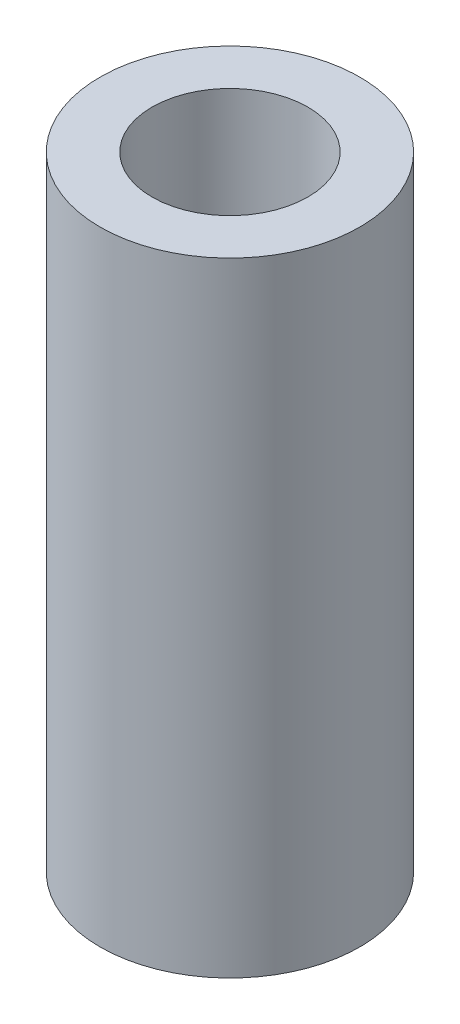
SolidWorks part; units mm, degrees
material "1060 合金"
ref_plane "前视基准面" through (0, 0, 0) normal (0, 0, 1) x (1, 0, 0)
ref_plane "上视基准面" through (0, 0, 0) normal (0, 1, 0) x (1, 0, 0)
ref_plane "右视基准面" through (0, 0, 0) normal (1, 0, 0) x (0, 0, -1)
other "Configuration Table"
sketch "草图1" plane through (0, 0, 0) normal (0, 1, 0) x (1, 0, 0)
  circle A0 centre (0, 0) radius 2.5
  circle A1 centre (0, 0) radius 1.5
  dimension "D1" = 3
  dimension "5" = 5
extrude "凸台-拉伸1" add sketch "草图1" along normal blind 12
